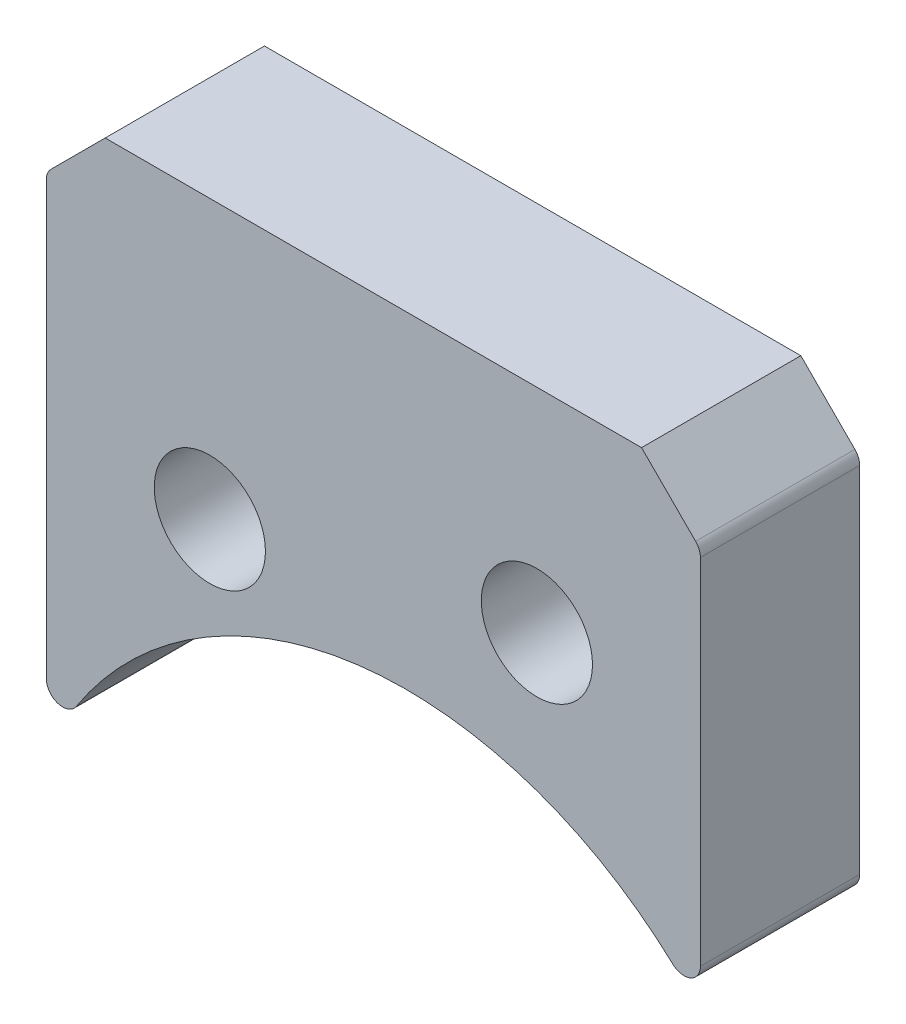
SolidWorks part; units mm, degrees
ref_plane "Front Plane" through (0, 0, 0) normal (0, 0, 1) x (1, 0, 0)
ref_plane "Top Plane" through (0, 0, 0) normal (0, 1, 0) x (1, 0, 0)
ref_plane "Right Plane" through (0, 0, 0) normal (1, 0, 0) x (0, 0, -1)
sketch "Sketch1" plane through (0, 0, 0) normal (0, 0, 1) x (1, 0, 0)
  line L0 (-20, 0) -> (0, 0)
  line L2 (-20, -17.2042) -> (-20, 0)
  line L4 (0, -14.0627) -> (0, 0)
  arc A0 (0, -14.0627) -> (-20, -17.2042) centre (-9, -22) ccw
  circle A1 centre (-15, -8.5) radius 1.7
  circle A2 centre (-5, -6.5) radius 1.7
  dimension "D4" = 22
  dimension "10.5" = 12
  dimension "D2" = 3.4
  dimension "D1" = 9
  dimension "D3" = 20
  dimension "D5" = 5
  dimension "D6" = 15
  dimension "D7" = 6.5
  dimension "D8" = 8.5
extrude "Boss-Extrude1" add sketch "Sketch1" along normal blind 4.87
chamfer "Chamfer1" distance 1.8 angle 45 2 edges at (0, 0, 2.435) (-20, 0, 2.435)
fillet "Fillet1" radius 0.5 4 edges at (-20, -1.8, 2.435) (0, -1.8, 2.435) (0, -14.0627, 2.435) (-20, -17.2042, 2.435)
